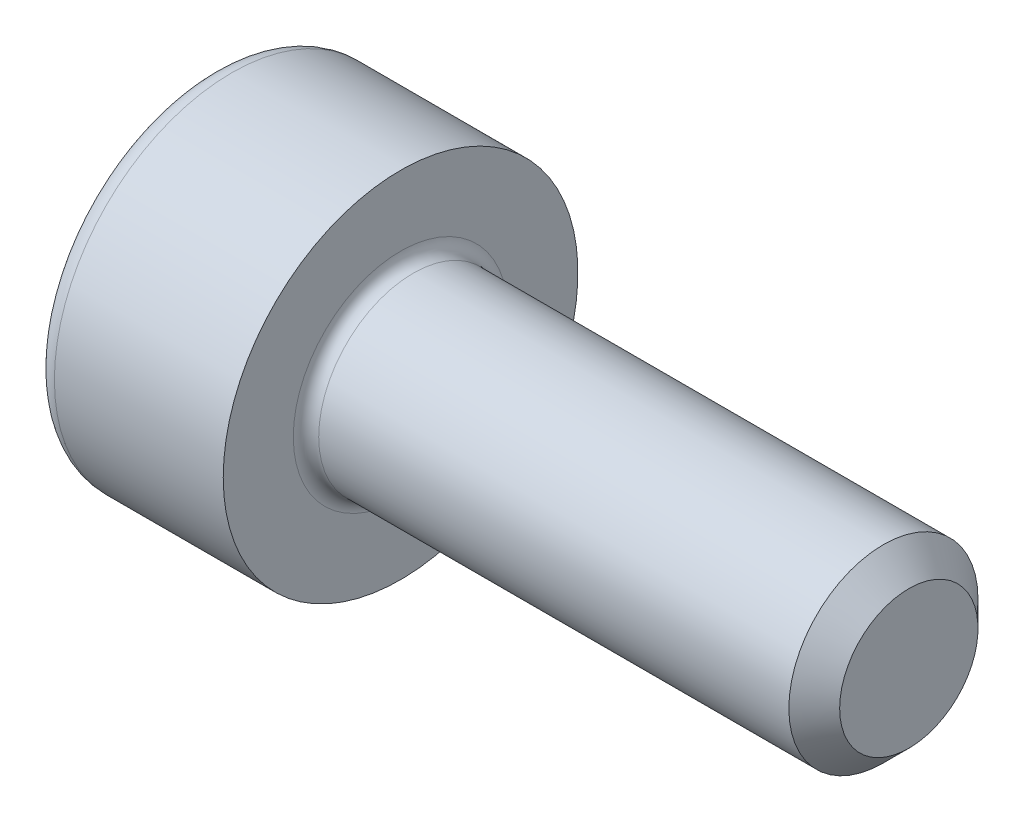
SolidWorks part; units mm, degrees
ref_plane "Спереди" through (0, 0, 0) normal (0, 0, 1) x (1, 0, 0)
ref_plane "Сверху" through (0, 0, 0) normal (0, 1, 0) x (1, 0, 0)
ref_plane "Справа" through (0, 0, 0) normal (1, 0, 0) x (0, 0, -1)
sketch "Sketch1" plane through (0, 0, 0) normal (0, 0, 1) x (1, 0, 0)
  line L0 (0, 0) -> (1.4887, 0)
  line L1 (1.4887, 0) -> (1.4887, 1.3957)
  line L2 (1.4887, 1.3957) -> (0, 1.3957)
  line L3 (0, 1.3957) -> (0, 0)
  line L4 (1.4887, 0) -> (5.4887, 0)
  line L5 (5.4887, 0) -> (5.4887, 0.7444)
  line L6 (5.4887, 0.7444) -> (1.4887, 0.7444)
  dimension "D1" = 4
revolve "Revolve1" add sketch "Sketch1" angle 360 about L0
fillet "Fillet1" radius 0.1 1 edges at (1.4887, 0, 0.7444)
fillet "Fillet2" radius 0.16 1 edges at (0, 0, 1.3957)
chamfer "Chamfer1" distance 0.2 angle 45 1 edges at (5.4887, 0, 0.7444)
sketch "Sketch2" plane through (0, 0, 0) normal (-1, 0, 0) x (0, 0, 1)
  line L1 (0, 0.8776) -> (-0.76, 0.4388)
  line L2 (-0.76, 0.4388) -> (-0.76, -0.4388)
  line L3 (-0.76, -0.4388) -> (0, -0.8776)
  line L4 (0, -0.8776) -> (0.76, -0.4388)
  line L5 (0.76, -0.4388) -> (0.76, 0.4388)
  line L6 (0.76, 0.4388) -> (0, 0.8776)
  circle A0 centre (0, 0) radius 0.76 construction
extrude "Extrude1" cut sketch "Sketch2" against normal blind 0.7
